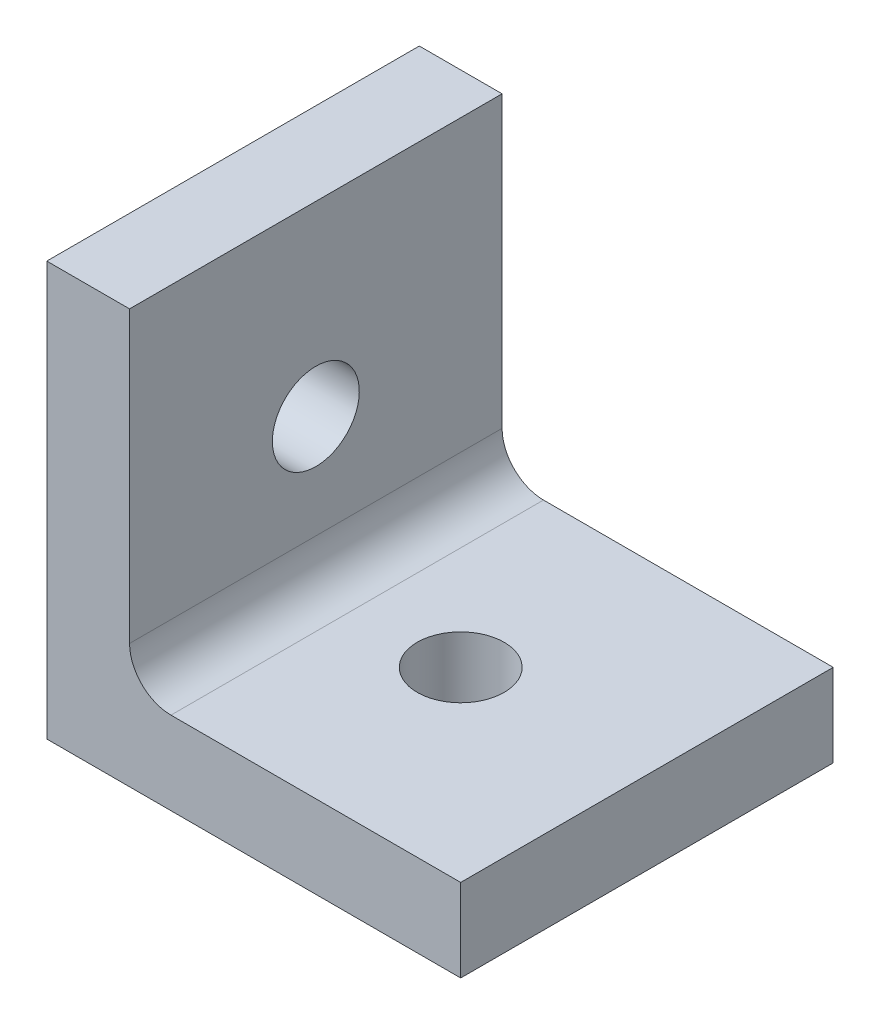
SolidWorks part; units mm, degrees
ref_plane "Płaszczyzna przednia" through (0, 0, 0) normal (0, 0, 1) x (1, 0, 0)
ref_plane "Płaszczyzna górna" through (0, 0, 0) normal (0, 1, 0) x (1, 0, 0)
ref_plane "Płaszczyzna prawa" through (0, 0, 0) normal (1, 0, 0) x (0, 0, -1)
sketch "Szkic1" plane through (0, 0, 0) normal (0, 0, 1) x (1, 0, 0)
  line L1 (0, 0) -> (20, 0)
  line L2 (0, 0) -> (0, 20)
  line L3 (0, 20) -> (4, 20)
  line L4 (20, 0) -> (20, 4)
  line L7 (20, 4) -> (4, 4)
  line L8 (4, 20) -> (4, 4)
  dimension "D1" = 20
  dimension "D2" = 20
  dimension "D3" = 16
  dimension "D4" = 16
extrude "Dodanie-wyciągnięcie1" add sketch "Szkic1" along normal blind 18
sketch "Szkic2" plane through (4, 0, 0) normal (1, 0, 0) x (0, 0, -1)
  line L0 (-18, 4) -> (-18, 20) construction
  line L1 (-18, 20) -> (0, 20) construction
  circle A0 centre (-9, 11) radius 2.1
  dimension "D1" = 4.2
  dimension "D2" = 9
  dimension "D3" = 9
extrude "Wytnij-wyciągnięcie1" cut sketch "Szkic2" against normal through all
sketch "Szkic3" plane through (0, 4, 0) normal (0, 1, 0) x (1, 0, 0)
  line L0 (20, -18) -> (20, 0) construction
  line L1 (20, 0) -> (4, 0) construction
  circle A0 centre (11, -9) radius 2.1
  dimension "D1" = 4.2
  dimension "D2" = 9
  dimension "D3" = 9
extrude "Wytnij-wyciągnięcie2" cut sketch "Szkic3" against normal through all
fillet "Zaokrąglenie1" radius 2 1 edges at (4, 4, 9)
